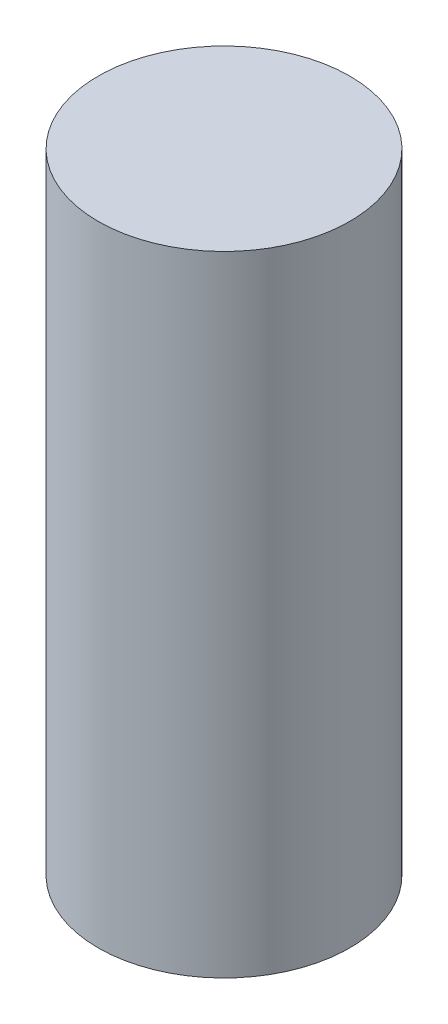
SolidWorks part; units mm, degrees
ref_plane "Front Plane" through (0, 0, 0) normal (0, 0, 1) x (1, 0, 0)
ref_plane "Top Plane" through (0, 0, 0) normal (0, 1, 0) x (1, 0, 0)
ref_plane "Right Plane" through (0, 0, 0) normal (1, 0, 0) x (0, 0, -1)
sketch "Sketch1" plane through (0, 0, 0) normal (0, 1, 0) x (1, 0, 0)
  circle A0 centre (0, 0) radius 8
  dimension "D1" = 16
extrude "Boss-Extrude1" add sketch "Sketch1" along normal blind 40
